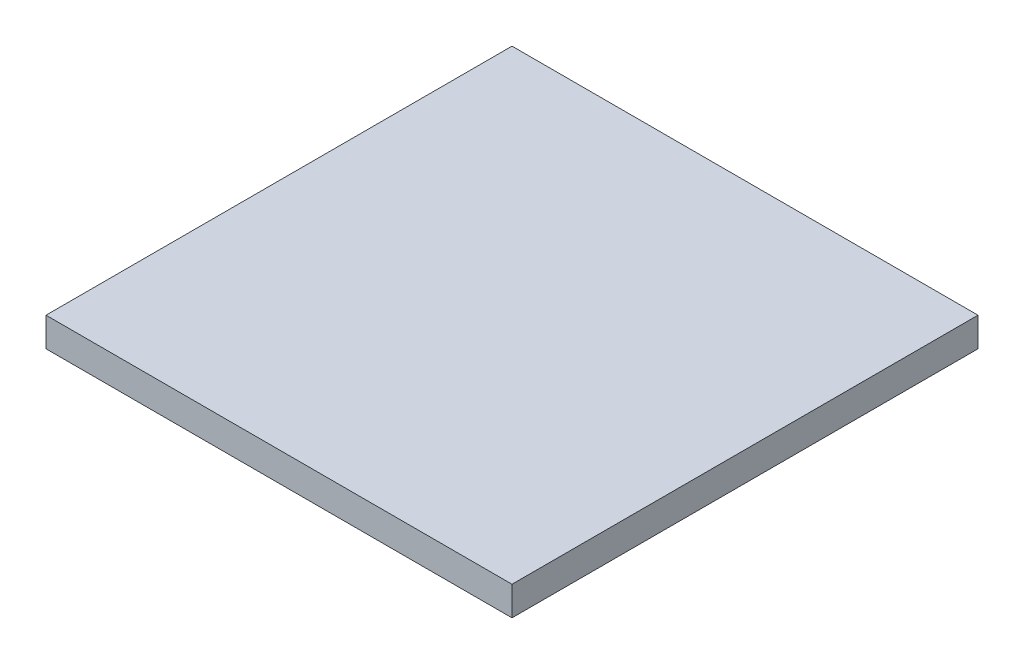
SolidWorks part; units mm, degrees
material "Pine"
ref_plane "Front Plane" through (0, 0, 0) normal (0, 0, 1) x (1, 0, 0)
ref_plane "Top Plane" through (0, 0, 0) normal (0, 1, 0) x (1, 0, 0)
ref_plane "Right Plane" through (0, 0, 0) normal (1, 0, 0) x (0, 0, -1)
sketch "Sketch1" plane through (0, 0, 0) normal (0, 1, 0) x (1, 0, 0)
  line L1 (0, 0) -> (1219.2, 0)
  line L2 (0, 0) -> (0, -609.6)
  line L3 (0, -609.6) -> (1219.2, -609.6)
  line L4 (1219.2, 0) -> (1219.2, -609.6)
  line L5 (0, 0) -> (1219.2, -609.6) construction
  line L6 (0, -609.6) -> (1219.2, 0) construction
  dimension "D1" = 1219.2
  dimension "D2" = 609.6
extrude "Boss-Extrude1" [suppressed] add sketch "Sketch1" along normal blind 38.1
sketch "Sketch2" plane through (0, 0, 0) normal (0, 1, 0) x (1, 0, 0)
  line L1 (0, 0) -> (304.8, 0)
  line L2 (0, 0) -> (0, -304.8)
  line L3 (0, -304.8) -> (304.8, -304.8)
  line L4 (304.8, 0) -> (304.8, -304.8)
  dimension "D1" = 304.8
  dimension "D2" = 304.8
extrude "Boss-Extrude2" add sketch "Sketch2" along normal blind 19.05
